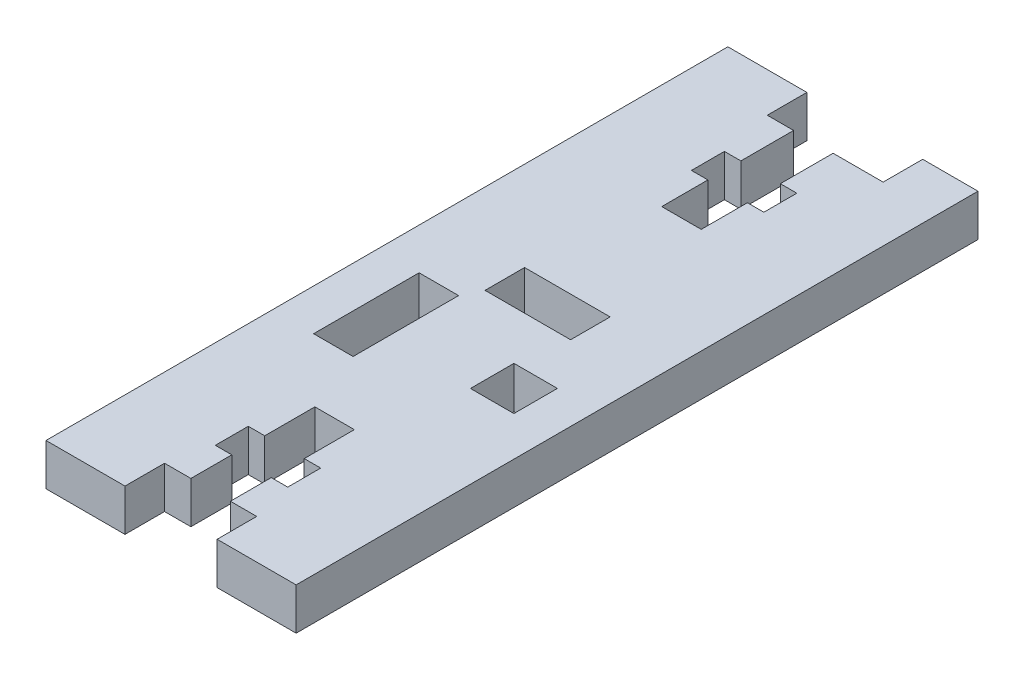
SolidWorks part; units mm, degrees
ref_plane "Front Plane" through (0, 0, 0) normal (0, 0, 1) x (1, 0, 0)
ref_plane "Top Plane" through (0, 0, 0) normal (0, 1, 0) x (1, 0, 0)
ref_plane "Right Plane" through (0, 0, 0) normal (1, 0, 0) x (0, 0, -1)
sketch "Sketch1" plane through (0, 0, 0) normal (0, 1, 0) x (1, 0, 0)
  line L0 (9.8429, -27.4833) -> (3.8536, -27.4833)
  line L1 (-9.1233, -27.4833) -> (-9.1233, 24.2185)
  line L2 (-9.1233, 24.2185) -> (-3.1341, 24.2185)
  line L3 (9.8429, 24.2185) -> (9.8429, -27.4833)
  line L4 (-3.1341, 24.2185) -> (-3.1341, 21.2185)
  line L5 (-3.1341, 21.2185) -> (-1.1376, 21.2185)
  line L6 (-1.1376, 21.2185) -> (-1.1376, 17.2183)
  line L7 (-1.1376, 17.2183) -> (-2.3854, 17.2183)
  line L8 (-2.3854, 17.2183) -> (-2.3854, 14.7184)
  line L9 (-2.3854, 14.7184) -> (-1.1376, 14.7184)
  line L10 (-1.1376, 14.7184) -> (-1.1376, 11.2182)
  line L11 (-1.1376, 11.2182) -> (1.8573, 11.2182)
  line L12 (1.8573, 11.2182) -> (1.8573, 14.7184)
  line L13 (1.8573, 14.7184) -> (3.1051, 14.7184)
  line L14 (3.1051, 14.7184) -> (3.1051, 17.2183)
  line L15 (3.1051, 17.2183) -> (1.8573, 17.2183)
  line L16 (1.8573, 17.2183) -> (1.8573, 21.2185)
  line L17 (1.8573, 21.2185) -> (5.6504, 21.2185)
  line L18 (5.6504, 21.2185) -> (5.6504, 24.2187)
  line L19 (-3.1341, -27.4833) -> (-3.1341, -24.4832)
  line L20 (-3.1341, -24.4832) -> (-1.1376, -24.4832)
  line L21 (-1.1376, -24.4832) -> (-3.1341, -24.4832)
  line L22 (3.8536, -24.4832) -> (1.8573, -24.4832)
  line L23 (1.8573, -24.4832) -> (3.8536, -24.4832)
  line L24 (3.8536, -24.4832) -> (3.8536, -27.4833)
  line L25 (4.1531, -0.9822) -> (4.1531, 2.0177)
  line L26 (4.1531, 2.0177) -> (-2.3354, 2.0177)
  line L27 (-2.3354, 2.0177) -> (-2.3354, -0.9822)
  line L28 (-2.3354, -0.9822) -> (4.1531, -0.9822)
  line L29 (1.8573, -24.4832) -> (1.8573, -21.3831)
  line L30 (1.8573, -21.3831) -> (3.1051, -21.3831)
  line L31 (3.1051, -21.3831) -> (3.1051, -18.883)
  line L32 (3.1051, -18.883) -> (1.8573, -18.883)
  line L33 (1.8573, -18.883) -> (1.8573, -15.0828)
  line L34 (1.8573, -15.0828) -> (-1.1376, -15.0828)
  line L35 (-1.1376, -15.0828) -> (-1.1376, -18.883)
  line L36 (-1.1376, -18.883) -> (-2.3854, -18.883)
  line L37 (-2.3854, -18.883) -> (-2.3854, -21.3831)
  line L38 (-2.3854, -21.3831) -> (-1.1376, -21.3831)
  line L39 (-1.1376, -21.3831) -> (-1.1376, -24.4832)
  line L40 (3.5542, -7.9784) -> (6.8484, -7.9784)
  line L41 (6.8484, -7.9784) -> (6.8484, -4.6781)
  line L42 (6.8484, -4.6781) -> (3.5542, -4.6781)
  line L43 (3.5542, -4.6781) -> (3.5542, -7.9784)
  line L44 (-5.9878, -10.3284) -> (-2.9932, -10.3284)
  line L45 (-2.9932, -10.3284) -> (-2.9932, -2.3281)
  line L46 (-2.9932, -2.3281) -> (-5.9878, -2.3281)
  line L47 (-5.9878, -2.3281) -> (-5.9878, -10.3284)
  line L48 (5.6504, 24.2185) -> (9.8429, 24.2185)
  line L49 (-3.1341, -27.4833) -> (-9.1233, -27.4833)
  point P52 (0, 0)
extrude "Boss-Extrude1" add sketch "Sketch1" along normal blind 3.175 contours L49 L19 L20 L39 L38 L37 L36 L35 L34 L33 L32 L31 L30 L29 L22 L24 L0 L3 L48 L18 L17 L16 L15 L14 L13 L12 L11 L10 L9 L8 L7 L6 L5 L4 L2 L1 L47 L46 L45 L44 L43 L42 L41 L40 L28 L27 L26 L25
